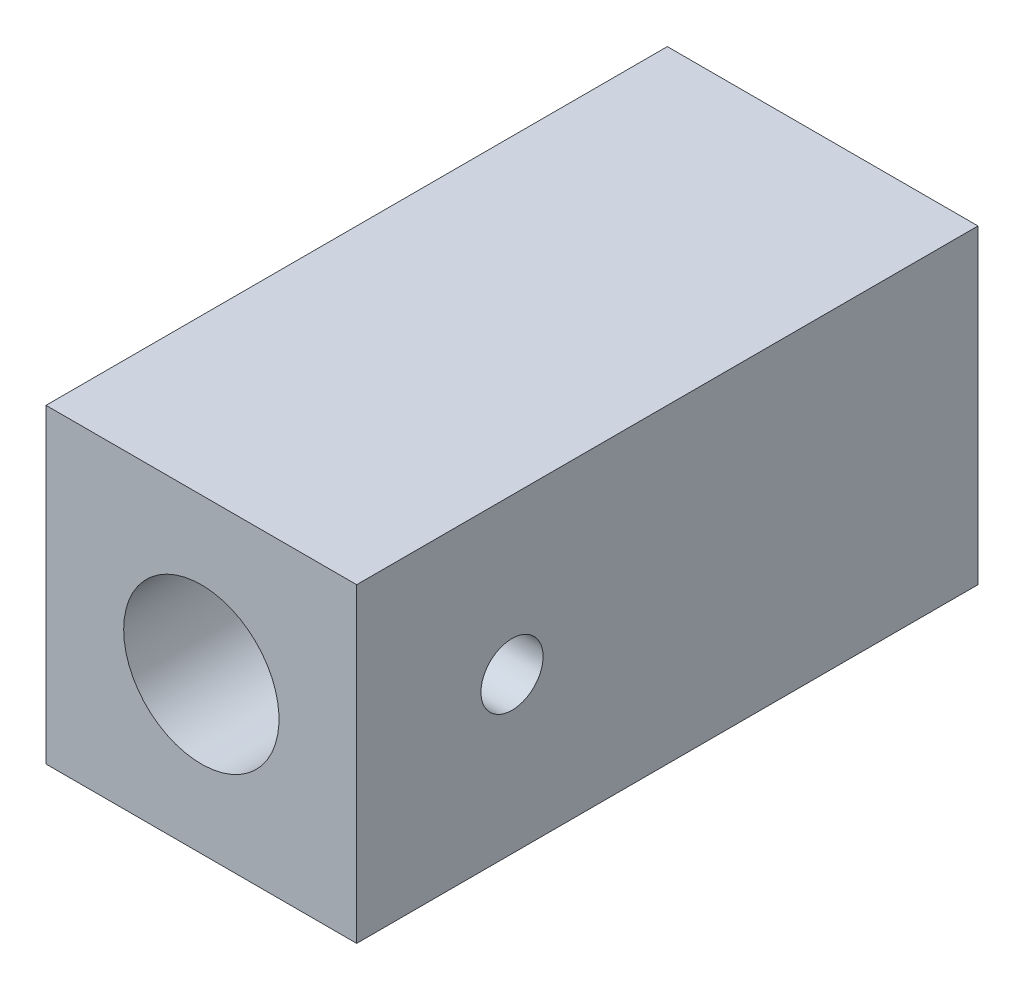
SolidWorks part; units mm, degrees
ref_plane "前视基准面" through (0, 0, 0) normal (0, 0, 1) x (1, 0, 0)
ref_plane "上视基准面" through (0, 0, 0) normal (0, 1, 0) x (1, 0, 0)
ref_plane "右视基准面" through (0, 0, 0) normal (1, 0, 0) x (0, 0, -1)
sketch "草图1" plane through (0, 0, 0) normal (0, 0, 1) x (1, 0, 0)
  line L1 (-5, -5) -> (5, -5)
  line L2 (-5, -5) -> (-5, 5)
  line L3 (-5, 5) -> (5, 5)
  line L4 (5, -5) -> (5, 5)
  line L5 (-5, -5) -> (5, 5) construction
  line L6 (-5, 5) -> (5, -5) construction
  point P0 (0, 0)
  dimension "D1" = 10
extrude "凸台-拉伸1" add sketch "草图1" along normal blind 10
sketch "草图2" plane through (0, 0, 10) normal (0, 0, 1) x (1, 0, 0)
  circle A0 centre (0, 0) radius 2.5
  dimension "D1" = 5
extrude "凸台-拉伸2" add sketch "草图2" along normal blind 5
sketch "草图3" plane through (5, 0, 0) normal (1, 0, 0) x (0, 0, -1)
  circle A0 centre (-5, 0) radius 1
  dimension "D1" = 2
extrude "凸台-拉伸3" add sketch "草图3" along normal blind 5
sketch "草图4" plane through (0, 0, 15) normal (0, 0, 1) x (1, 0, 0)
  circle A0 centre (0, 0) radius 2.5
extrude "切除-拉伸1" cut sketch "草图4" against normal blind 30
sketch "草图5" plane through (10, 0, 0) normal (1, 0, 0) x (0, 0, -1)
  circle A1 centre (-5, 0) radius 1
extrude "切除-拉伸2" cut sketch "草图5" against normal blind 30
sketch "草图6" plane through (0, 0, 10) normal (0, 0, 1) x (1, 0, 0)
  line L1 (-5, 5) -> (5, 5)
  line L2 (-5, 5) -> (-5, -5)
  line L3 (-5, -5) -> (5, -5)
  line L4 (5, 5) -> (5, -5)
sketch "草图9" plane through (0, 0, 0) normal (0, 0, -1) x (-1, 0, 0)
  line L1 (-5, 5) -> (5, 5)
  line L2 (-5, 5) -> (-5, -5)
  line L3 (-5, -5) -> (5, -5)
  line L4 (5, 5) -> (5, -5)
extrude "凸台-拉伸5" add sketch "草图9" along normal blind 10
sketch "草图10" plane through (0, 0, -10) normal (0, 0, -1) x (-1, 0, 0)
  circle A0 centre (0, 0) radius 2
  dimension "D1" = 4
extrude "切除-拉伸4" cut sketch "草图10" against normal blind 20
